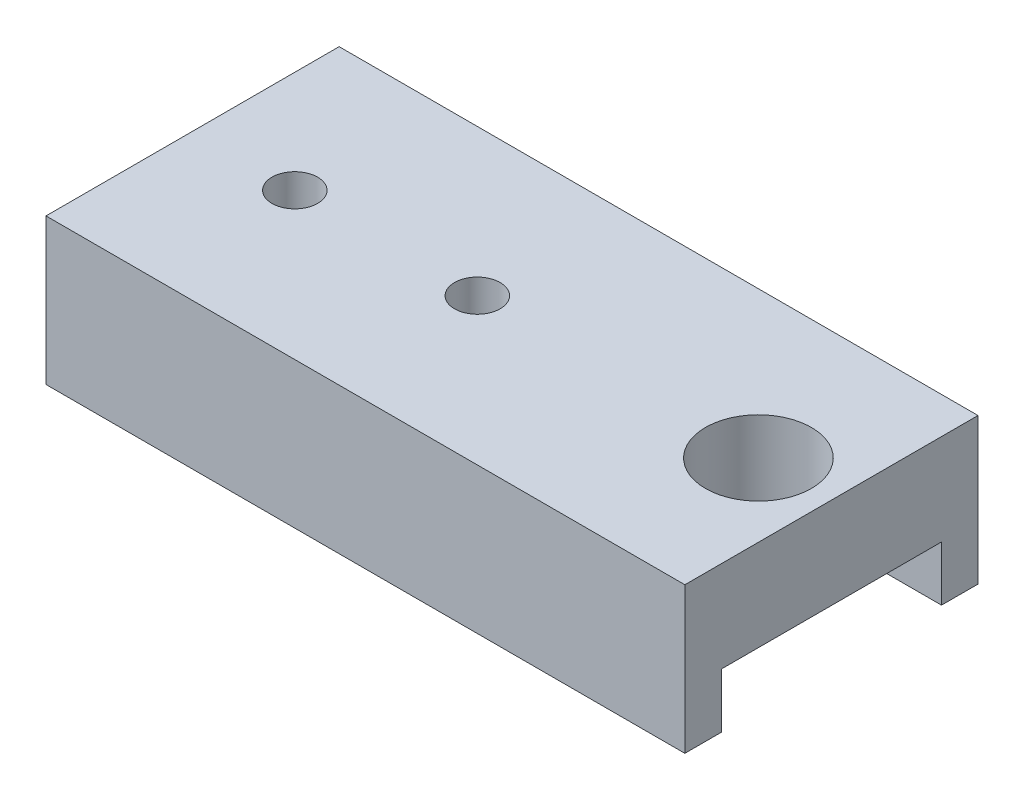
SolidWorks part; units mm, degrees
ref_plane "Front Plane" through (0, 0, 0) normal (0, 0, 1) x (1, 0, 0)
ref_plane "Top Plane" through (0, 0, 0) normal (0, 1, 0) x (1, 0, 0)
ref_plane "Right Plane" through (0, 0, 0) normal (1, 0, 0) x (0, 0, -1)
sketch "Sketch1" plane through (0, 0, 0) normal (0, 1, 0) x (1, 0, 0)
  line L1 (17.5, -6.03) -> (-17.5, -6.03)
  line L2 (17.5, -6.03) -> (17.5, 6.03)
  line L3 (17.5, 6.03) -> (-17.5, 6.03)
  line L4 (-17.5, -6.03) -> (-17.5, 6.03)
  line L5 (17.5, -6.03) -> (-17.5, 6.03) construction
  line L6 (17.5, 6.03) -> (-17.5, -6.03) construction
  point P0 (0, 0)
  dimension "D1" = 12.06
  dimension "D2" = 35
extrude "Boss-Extrude1" add sketch "Sketch1" along normal blind 5
sketch "Sketch2" plane through (0, 5, 0) normal (0, 1, 0) x (1, 0, 0)
  line L0 (17.5, -6.03) -> (17.5, 6.03) construction
  point P0 (13.5, 0)
  point P1 (-1.9, 0)
  point P2 (-11.9, 0)
  dimension "D1" = 10
  dimension "D2" = 4
  dimension "D3" = 25.4
hole_wizard "M5 Clearance Hole1" positions "Sketch3" profile "Sketch4" hole size "M5" standard "ANSI Metric" end condition through all
sketch "Sketch3" plane through (0, 5, 0) normal (0, 1, 0) x (1, 0, 0)
  point P0 (13.5, 0)
sketch "Sketch4" plane through (13.5, 5, 0) normal (1, 0, 0) x (0, 0, 1)
  line L0 (0, 0) -> (0, 5)
  line L1 (0, 5) -> (2.9, 5)
  line L2 (2.9, 5) -> (2.9, 0)
  line L5 (2.9, 0) -> (0, 0)
  line L11 (0, -6.35) -> (0, 107.95) construction
  dimension "Thru Hole Dia." = 5.8
  dimension "Thru Hole Depth" = 5
hole_wizard "Tap Drill for M3x0.5 Tap1" positions "Sketch5" profile "Sketch6" hole size "M3x0.5" standard "ANSI Metric" end condition through all
sketch "Sketch5" plane through (0, 5, 0) normal (0, 1, 0) x (1, 0, 0)
  point P0 (-1.9, 0)
  point P3 (-11.9, 0)
sketch "Sketch6" plane through (-1.9, 5, 0) normal (1, 0, 0) x (0, 0, 1)
  line L0 (0, 0) -> (0, 5)
  line L1 (0, 5) -> (1.25, 5)
  line L2 (1.25, 5) -> (1.25, 0)
  line L5 (1.25, 0) -> (0, 0)
  line L11 (0, -6.35) -> (0, 107.95) construction
  dimension "Thru Hole Dia." = 2.5
  dimension "Thru Hole Depth" = 5
sketch "Sketch7" plane through (0, 0, -6.03) normal (0, 0, -1) x (-1, 0, 0)
  line L0 (-17.5, 5) -> (-17.5, 0) construction
  line L1 (17.5, 5) -> (-17.5, 5)
  line L2 (17.5, 5) -> (17.5, -3)
  line L3 (17.5, -3) -> (-17.5, -3)
  line L4 (-17.5, 5) -> (-17.5, -3)
  line L5 (-17.5, 0) -> (17.5, 0) construction
  dimension "D1" = 0
  dimension "D2" = 3
extrude "Boss-Extrude2" add sketch "Sketch7" along normal blind 2
mirror "Mirror1" about plane through (0, 0, 0) normal (0, 0, 1) of bodies 104
